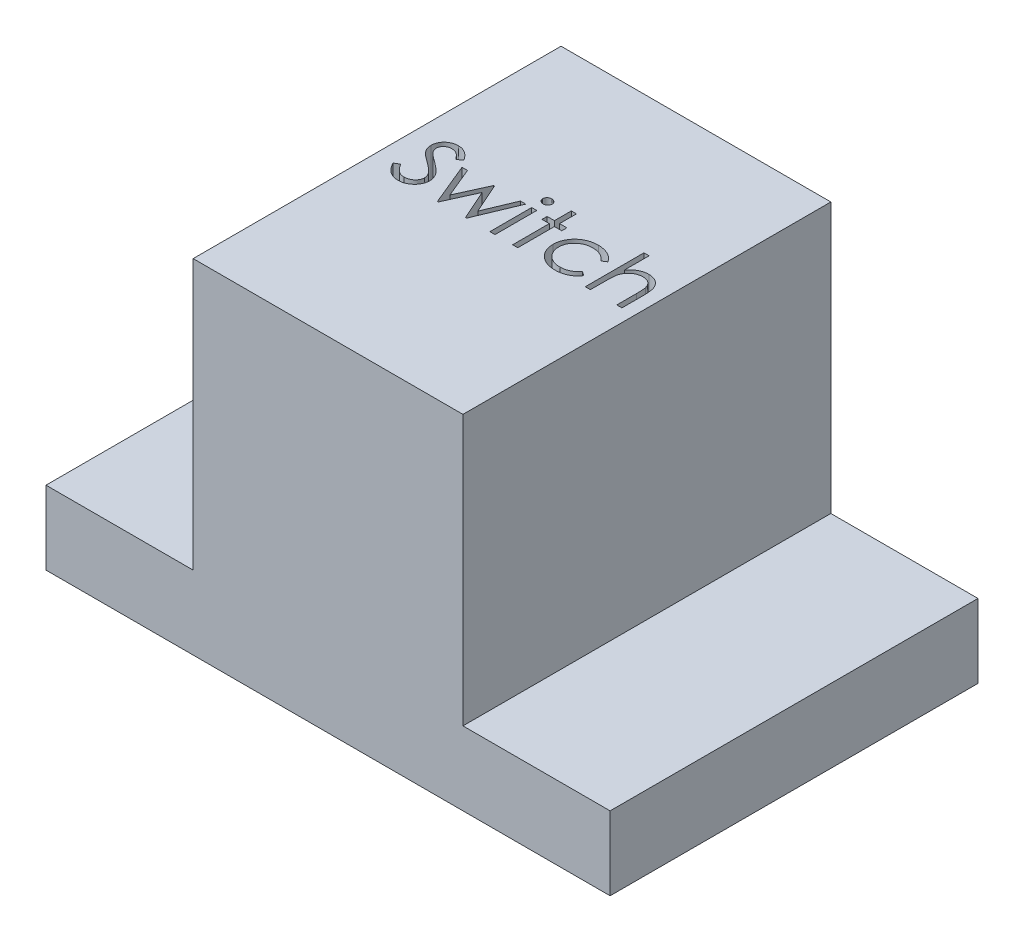
SolidWorks part; units mm, degrees
ref_plane "Front Plane" through (0, 0, 0) normal (0, 0, 1) x (1, 0, 0)
ref_plane "Top Plane" through (0, 0, 0) normal (0, 1, 0) x (1, 0, 0)
ref_plane "Right Plane" through (0, 0, 0) normal (1, 0, 0) x (0, 0, -1)
sketch "Sketch1" plane through (0, 0, 0) normal (0, 1, 0) x (1, 0, 0)
  line L1 (0, 0) -> (73.025, 0)
  line L2 (0, 0) -> (0, 47.625)
  line L3 (0, 47.625) -> (73.025, 47.625)
  line L4 (73.025, 0) -> (73.025, 47.625)
  dimension "D1" = 47.625
  dimension "D2" = 73.025
extrude "Boss-Extrude1" add sketch "Sketch1" along normal blind 44.45
sketch "Sketch2" plane through (0, 44.45, 0) normal (0, 1, 0) x (1, 0, 0)
  line L0 (73.025, 47.625) -> (0, 47.625) construction
  line L1 (0, 0) -> (19.05, 0)
  line L2 (0, 0) -> (0, 47.625)
  line L3 (0, 47.625) -> (19.05, 47.625)
  line L4 (19.05, 0) -> (19.05, 47.625)
  line L6 (73.025, 0) -> (53.975, 0)
  line L7 (73.025, 0) -> (73.025, 47.625)
  line L8 (73.025, 47.625) -> (53.975, 47.625)
  line L9 (53.975, 0) -> (53.975, 47.625)
  dimension "D1" = 19.05
  dimension "D2" = 19.05
extrude "Cut-Extrude1" cut sketch "Sketch2" against normal blind 34.925
sketch "Sketch3" plane through (0, 44.45, 0) normal (0, 1, 0) x (1, 0, 0)
  line L0 (19.05, 0) -> (19.05, 47.625) construction
  line L1 (19.05, 0) -> (53.975, 0) construction
  text T0 "Switch" font "Century Gothic" height in points 28
  dimension "D1" = 2.032
  dimension "D2" = 22.225
extrude "Cut-Extrude2" cut sketch "Sketch3" against normal through all
